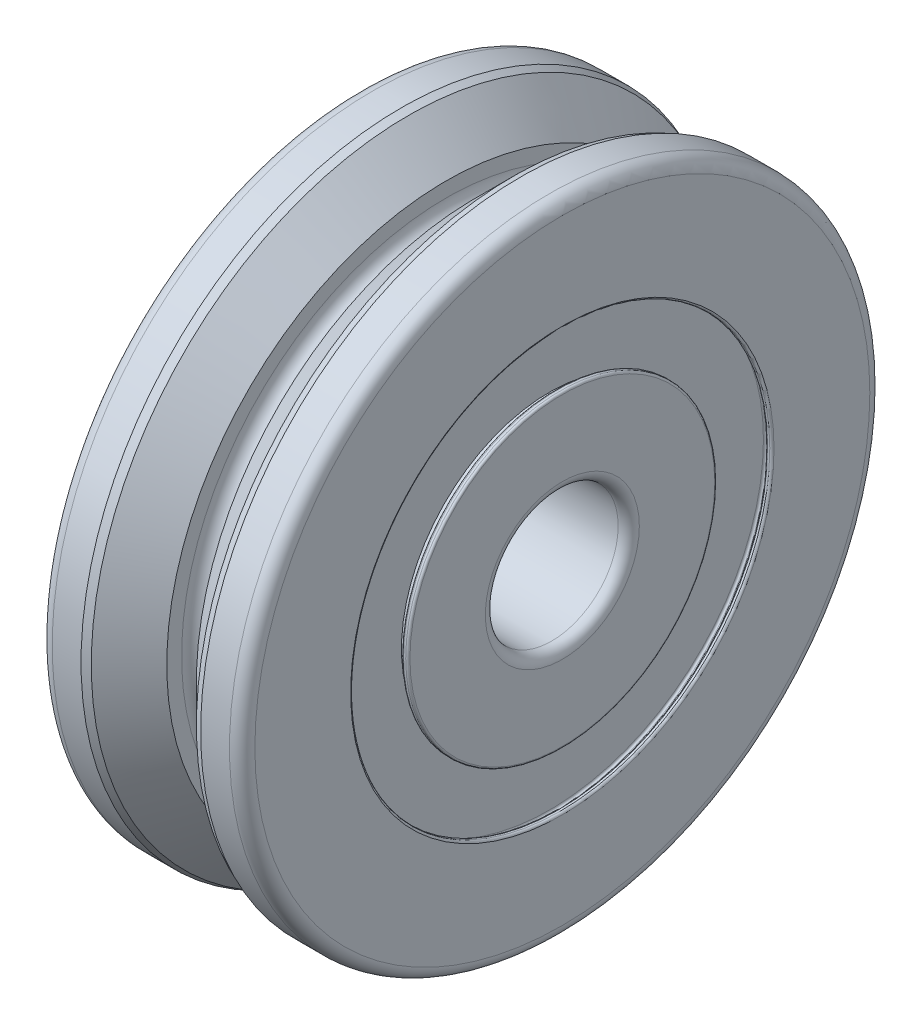
SolidWorks part; units mm, degrees
material "Cast Stainless Steel"
ref_plane "Front Plane" through (0, 0, 0) normal (0, 0, 1) x (1, 0, 0)
ref_plane "Top Plane" through (0, 0, 0) normal (0, 1, 0) x (1, 0, 0)
ref_plane "Right Plane" through (0, 0, 0) normal (1, 0, 0) x (0, 0, -1)
sketch "Sketch1" plane through (0, 0, 0) normal (0, 0, 1) x (1, 0, 0)
  line L0 (-4.8641, 7.3152) -> (-4.8641, 3.6957)
  line L1 (-4.3561, 3.1877) -> (4.3561, 3.1877)
  line L2 (4.8641, 3.6957) -> (4.8641, 7.3152)
  line L3 (4.7625, 7.4168) -> (4.6609, 7.4168)
  line L4 (4.5593, 7.3152) -> (4.5593, 7.112)
  line L5 (4.5593, 7.112) -> (4.2545, 7.112)
  line L6 (4.2545, 7.112) -> (4.2545, 10.2616)
  line L7 (4.3561, 10.3632) -> (4.5593, 10.3632)
  line L8 (4.5593, 10.3632) -> (4.5593, 10.16)
  line L9 (4.6609, 10.0584) -> (4.7625, 10.0584)
  line L10 (4.8641, 10.16) -> (4.8641, 14.7574)
  line L11 (4.2545, 15.367) -> (2.8699, 15.367)
  line L12 (2.8699, 15.367) -> (2.523, 15.2233)
  line L13 (2.523, 15.2233) -> (0.7112, 13.4115)
  line L14 (0.7112, 13.4115) -> (0.7112, 12.7)
  line L15 (-0.7112, 12.7) -> (-0.7112, 13.4115)
  line L16 (-0.7112, 13.4115) -> (-2.523, 15.2233)
  line L17 (-2.523, 15.2233) -> (-2.8699, 15.367)
  line L18 (-2.8699, 15.367) -> (-4.2545, 15.367)
  line L19 (-4.8641, 14.7574) -> (-4.8641, 10.16)
  line L20 (-4.7625, 10.0584) -> (-4.6609, 10.0584)
  line L21 (-4.5593, 10.16) -> (-4.5593, 10.3632)
  line L22 (-4.5593, 10.3632) -> (-4.3561, 10.3632)
  line L23 (-4.2545, 10.2616) -> (-4.2545, 7.112)
  line L24 (-4.2545, 7.112) -> (-4.5593, 7.112)
  line L25 (-4.5593, 7.112) -> (-4.5593, 7.3152)
  line L26 (-4.6609, 7.4168) -> (-4.7625, 7.4168)
  line L27 (-4.8641, 0) -> (4.8641, 0) construction
  arc A0 (-4.7625, 7.4168) -> (-4.8641, 7.3152) centre (-4.7625, 7.3152) ccw
  arc A1 (-4.8641, 3.6957) -> (-4.3561, 3.1877) centre (-4.3561, 3.6957) ccw
  arc A2 (4.3561, 3.1877) -> (4.8641, 3.6957) centre (4.3561, 3.6957) ccw
  arc A3 (4.8641, 7.3152) -> (4.7625, 7.4168) centre (4.7625, 7.3152) ccw
  arc A4 (4.6609, 7.4168) -> (4.5593, 7.3152) centre (4.6609, 7.3152) ccw
  arc A5 (4.2545, 10.2616) -> (4.3561, 10.3632) centre (4.3561, 10.2616) cw
  arc A6 (4.5593, 10.16) -> (4.6609, 10.0584) centre (4.6609, 10.16) ccw
  arc A7 (4.7625, 10.0584) -> (4.8641, 10.16) centre (4.7625, 10.16) ccw
  arc A8 (4.8641, 14.7574) -> (4.2545, 15.367) centre (4.2545, 14.7574) ccw
  arc A9 (0.7112, 12.7) -> (-0.7112, 12.7) centre (0, 12.7) cw
  arc A10 (-4.2545, 15.367) -> (-4.8641, 14.7574) centre (-4.2545, 14.7574) ccw
  arc A11 (-4.8641, 10.16) -> (-4.7625, 10.0584) centre (-4.7625, 10.16) ccw
  arc A12 (-4.6609, 10.0584) -> (-4.5593, 10.16) centre (-4.6609, 10.16) ccw
  arc A13 (-4.3561, 10.3632) -> (-4.2545, 10.2616) centre (-4.3561, 10.2616) cw
  arc A14 (-4.5593, 7.3152) -> (-4.6609, 7.4168) centre (-4.6609, 7.3152) ccw
revolve "Revolve1" add sketch "Sketch1" angle 360 about L27
